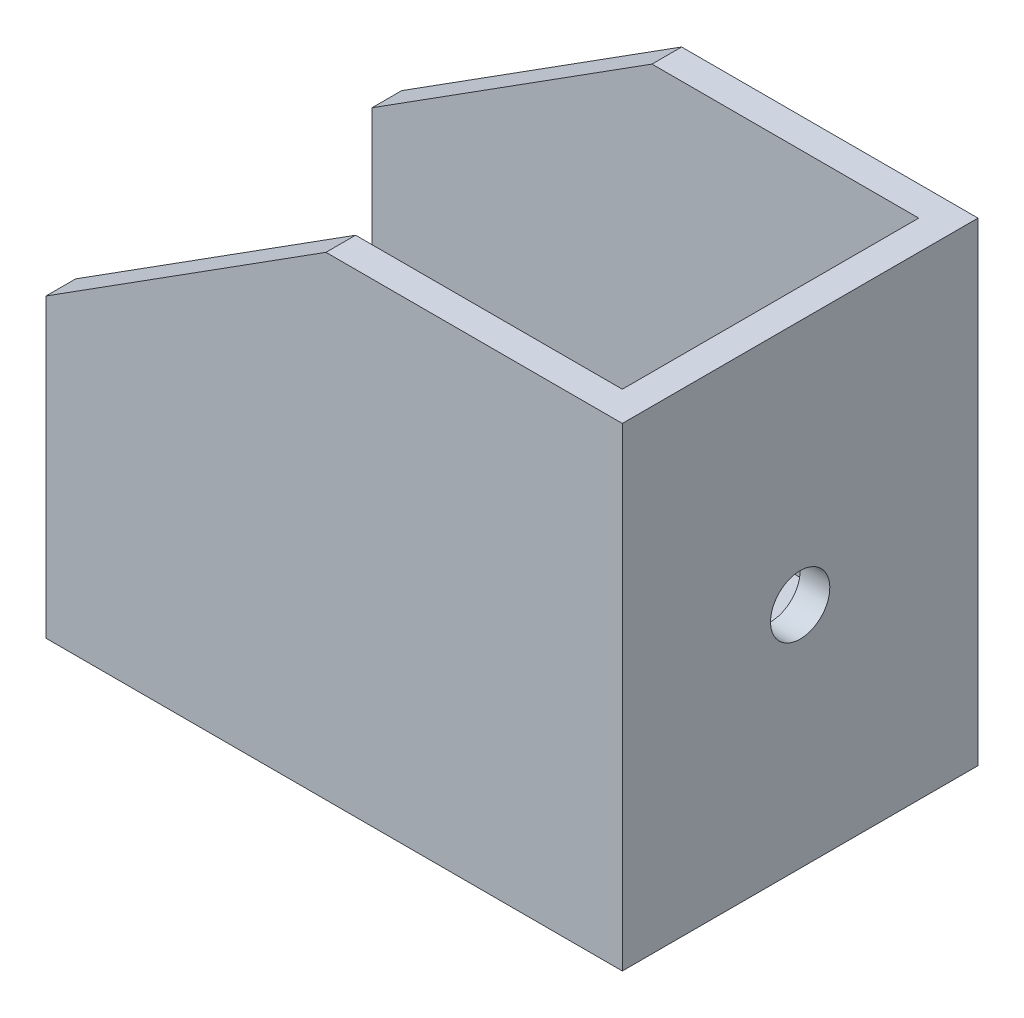
SolidWorks part; units mm, degrees
ref_plane "Front Plane" through (0, 0, 0) normal (0, 0, 1) x (1, 0, 0)
ref_plane "Top Plane" through (0, 0, 0) normal (0, 1, 0) x (1, 0, 0)
ref_plane "Right Plane" through (0, 0, 0) normal (1, 0, 0) x (0, 0, -1)
sketch "Sketch1" plane through (0, 0, 0) normal (0, 0, 1) x (1, 0, 0)
  line L0 (97.2259, 0) -> (47.2259, 0)
  line L2 (0, -29.9894) -> (0, -80)
  line L3 (0, -80) -> (97.2259, -80)
  line L4 (97.2259, 0) -> (97.2259, -80)
  line L5 (47.2259, 0) -> (0, -29.9894)
  dimension "D1" = 50
  dimension "D2" = 80
  dimension "D3" = 50.0106
extrude "Boss-Extrude1" add sketch "Sketch1" along normal blind 60
sketch "Sketch3" plane through (0, 0, 0) normal (-1, 0, 0) x (0, 0, 1)
  line L0 (0, -29.9894) -> (0, -80) construction
  line L1 (5, -62.5) -> (55, -62.5)
  line L2 (5, -62.5) -> (5, -5)
  line L3 (5, -5) -> (55, -5)
  line L4 (55, -62.5) -> (55, -5)
  line L5 (60, -29.9894) -> (60, -80) construction
  line L6 (60, -80) -> (0, -80) construction
  line L7 (60, 0) -> (0, 0) construction
  dimension "D1" = 5
  dimension "D2" = 5
  dimension "D3" = 17.5
  dimension "D4" = 5
extrude "Cut-Extrude6" cut sketch "Sketch3" against normal blind 80
sketch "Sketch9" plane through (80, 0, 0) normal (-1, 0, 0) x (0, 0, 1)
  line L0 (5, -62.5) -> (55, -62.5) construction
  line L1 (5, -62.5) -> (5, -29.9894) construction
  circle A0 centre (30, -41.5) radius 5
  dimension "D3" = 10
  dimension "D1" = 21
  dimension "D2" = 25
extrude "Cut-Extrude7" cut sketch "Sketch9" against normal blind 80
sketch "Sketch10" plane through (0, 0, 0) normal (0, 1, 0) x (1, 0, 0)
  line L0 (80, -5) -> (0, -5) construction
  line L1 (30.7088, -5) -> (92.2259, -5)
  line L2 (30.7088, -5) -> (30.7088, -55)
  line L3 (30.7088, -55) -> (92.2259, -55)
  line L4 (92.2259, -5) -> (92.2259, -55)
  line L5 (97.2259, -60) -> (97.2259, 0) construction
  line L7 (97.2259, -60) -> (47.2259, -60) construction
  dimension "D1" = 5
  dimension "D2" = 5
extrude "Cut-Extrude8" cut sketch "Sketch10" against normal blind 62.5
sketch "Sketch13" plane through (0, -62.5, 0) normal (0, 1, 0) x (1, 0, 0)
  line L0 (92.2259, -5) -> (0, -5) construction
  line L1 (0, -5) -> (0, -55) construction
  line L2 (92.2259, -5) -> (47.2259, -5) construction
  line L3 (92.2259, -55) -> (92.2259, -5) construction
  line L4 (92.2259, -55) -> (0, -55) construction
  circle A0 centre (10, -15) radius 1.5
  circle A1 centre (82.2259, -15) radius 1.5
  circle A2 centre (10, -45) radius 1.5
  circle A3 centre (82.2259, -45) radius 1.5
  dimension "D6" = 3
  dimension "D7" = 3
  dimension "D8" = 3
  dimension "D9" = 3
  dimension "D1" = 10
  dimension "D2" = 10
  dimension "D3" = 10
  dimension "D4" = 10
  dimension "D5" = 10
extrude "Cut-Extrude9" cut sketch "Sketch13" against normal through all
